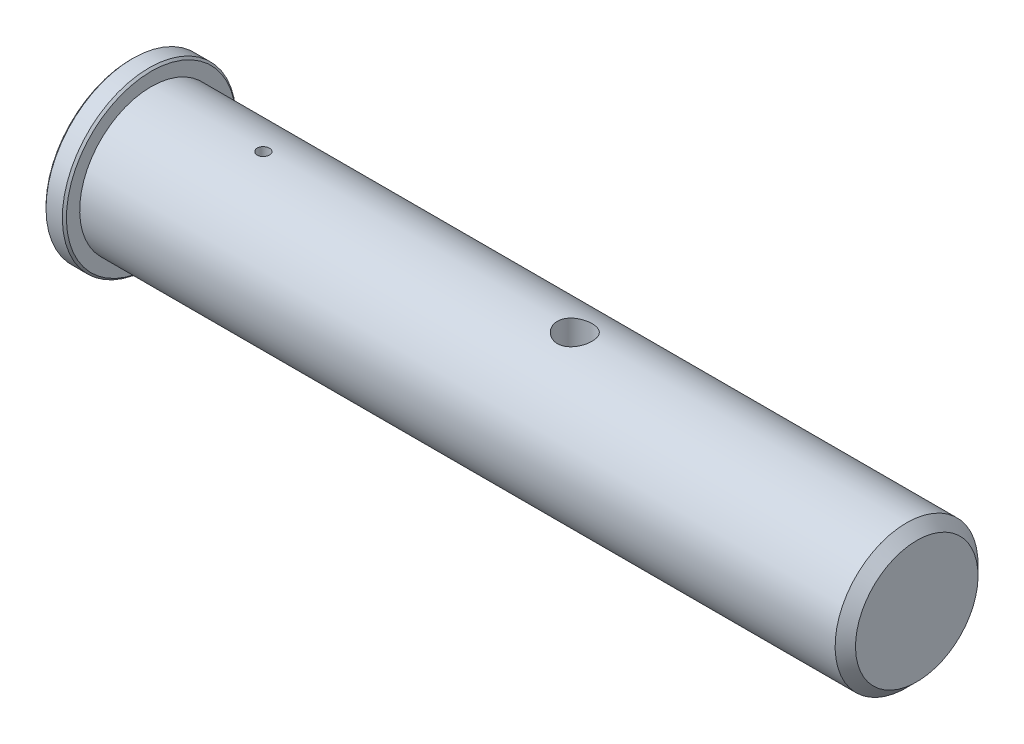
SolidWorks part; units mm, degrees
material "45"
ref_plane "前视基准面" through (0, 0, 0) normal (0, 0, 1) x (1, 0, 0)
ref_plane "上视基准面" through (0, 0, 0) normal (0, 1, 0) x (1, 0, 0)
ref_plane "右视基准面" through (0, 0, 0) normal (1, 0, 0) x (0, 0, -1)
sketch "草图1" plane through (0, 0, 0) normal (0, 0, 1) x (1, 0, 0)
  line L0 (0, 0) -> (0, 42.5)
  line L1 (0, 42.5) -> (10, 42.5)
  line L2 (10, 42.5) -> (10, 35)
  line L6 (385, 0) -> (0, 0)
  line L7 (10, 35) -> (385, 35)
  line L9 (385, 35) -> (385, 0)
  dimension "D4" = 35
  dimension "D1" = 10
  dimension "D2" = 42.5
  dimension "D3" = 375
revolve "旋转1" add sketch "草图1" angle 360 about L6
chamfer "倒角1" distance 1 angle 45 2 edges at (0, 42.5, 0) (10, 42.5, 0)
hole_wizard "Ø8.0 (8) 直径孔1" positions "3D草图1" profile "草图2" hole size "Ø8.0" standard "GB"
sketch3d "3D草图1"
  circle A0 centre (0, 0, 0) radius 41.5 construction
  point P0 (0, 0, 0)
  point P6 (-41.5, 0, 0)
sketch "草图2" plane through (0, 0, 0) normal (0, 1, 0) x (0, 0, 1)
  line L0 (0, 0) -> (0, 72.4034)
  line L1 (0, 72.4034) -> (4, 70)
  line L2 (4, 70) -> (4, 0)
  line L5 (4, 0) -> (0, 0)
  line L10 (0, 72.4034) -> (-4, 70) construction
  line L11 (0, -6.35) -> (0, 107.95) construction
  dimension "孔直径" = 8
  dimension "孔深度" = 70
  dimension "导头角度" = 118
chamfer "倒角2" distance 5 angle 45 1 edges at (385, 35, 0)
hole_wizard "M10x1.0 螺纹孔1" positions "3D草图2" profile "草图3" tap size "M10x1.0" standard "GB"
sketch3d "3D草图2"
  circle A0 centre (0, 0, 0) radius 41.5 construction
  point P0 (0, 0, 0)
  point P5 (-41.5, 0, 0)
cosmetic thread "孔螺蚊线1"
sketch "草图3" plane through (0, 0, 0) normal (0, 1, 0) x (0, 0, 1)
  line L0 (0, 0) -> (0, 17.7039)
  line L1 (0, 17.7039) -> (4.5, 15)
  line L2 (4.5, 15) -> (4.5, 0)
  line L5 (4.5, 0) -> (0, 0)
  line L10 (0, 17.7039) -> (-4.5, 15) construction
  line L11 (0, -6.35) -> (0, 107.95) construction
  dimension "螺纹孔钻头直径" = 9
  dimension "螺纹孔钻头深度" = 15
  dimension "导头角度" = 118
ref_plane "基准面1" through (0, 35, 0) normal (0, 1, 0) x (1, 0, 0)
hole_wizard "Ø6.0 (6) 直径孔4" positions "草图6" profile "草图7" hole size "Ø6.0" standard "GB"
sketch "草图6" plane through (0, 35, 0) normal (0, 1, 0) x (1, 0, 0)
  line L2 (10, -35) -> (380, -35) construction
  line L3 (10, -35) -> (10, 35) construction
  point P0 (65, 0)
  dimension "D1" = 35
  dimension "D2" = 55
sketch "草图7" plane through (65, 35, 0) normal (1, 0, 0) x (0, 0, 1)
  line L0 (0, 0) -> (0, 36.8026)
  line L1 (0, 36.8026) -> (3, 35)
  line L2 (3, 35) -> (3, 0)
  line L5 (3, 0) -> (0, 0)
  line L10 (0, 36.8026) -> (-3, 35) construction
  line L11 (0, -6.35) -> (0, 107.95) construction
  dimension "孔直径" = 6
  dimension "孔深度" = 35
  dimension "导头角度" = 118
sketch "草图8" plane through (0, 0, 0) normal (0, 1, 0) x (1, 0, 0)
  line L0 (10, -35) -> (10, 35) construction
  line L1 (10, -35) -> (380, -35) construction
  circle A0 centre (217.5, 0) radius 8.5
  dimension "D1" = 207.5
  dimension "D2" = 17
  dimension "D3" = 35
extrude "切除-拉伸1" cut sketch "草图8" against normal mid plane 70
